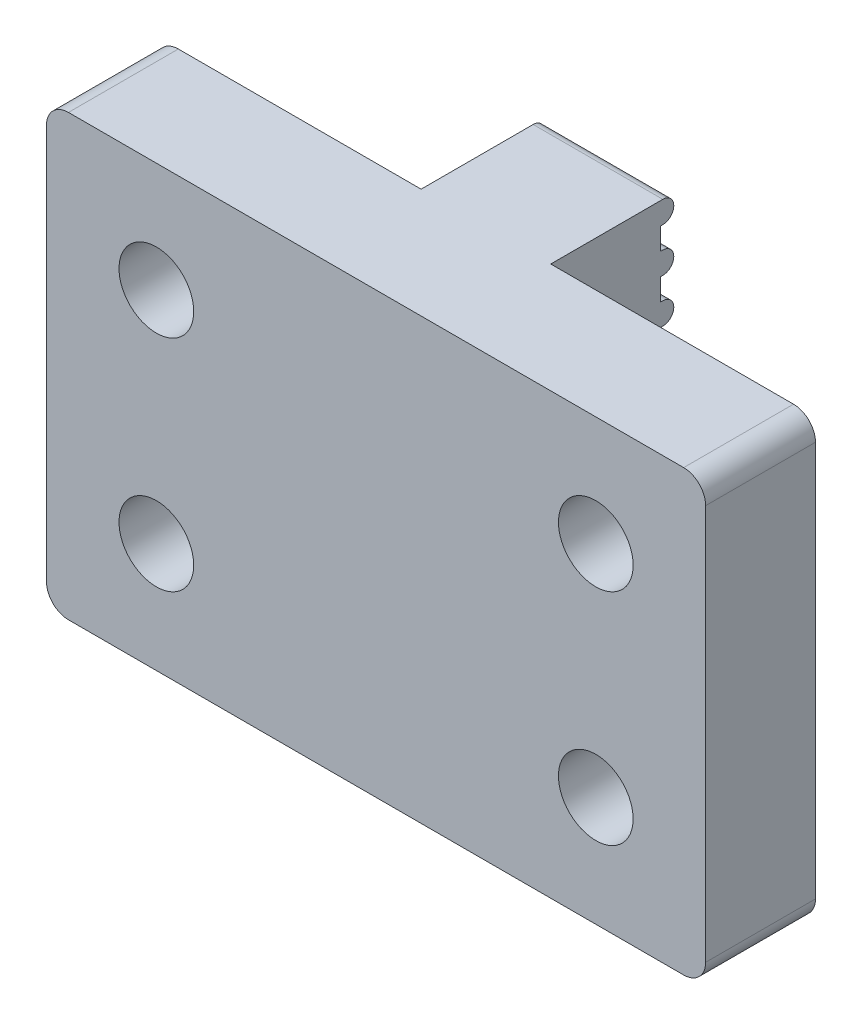
SolidWorks part; units mm, degrees
ref_plane "Front Plane" through (0, 0, 0) normal (0, 0, 1) x (1, 0, 0)
ref_plane "Top Plane" through (0, 0, 0) normal (0, 1, 0) x (1, 0, 0)
ref_plane "Right Plane" through (0, 0, 0) normal (1, 0, 0) x (0, 0, -1)
sketch "Master Sketch" plane through (0, 0, 0) normal (0, 0, 1) x (1, 0, 0)
  line L0 (-10, 5) -> (10, 5) construction
  line L1 (-2.95, -10) -> (2.95, -10)
  line L2 (-2.95, -10) -> (-2.95, 10)
  line L3 (-2.95, 10) -> (2.95, 10)
  line L4 (2.95, -10) -> (2.95, 10)
  line L5 (-2.95, -10) -> (2.95, 10) construction
  line L6 (-2.95, 10) -> (2.95, -10) construction
  line L7 (-15, -10) -> (15, -10)
  line L8 (-15, -10) -> (-15, 10)
  line L9 (-15, 10) -> (15, 10)
  line L10 (15, -10) -> (15, 10)
  line L11 (-15, -10) -> (15, 10) construction
  line L12 (-15, 10) -> (15, -10) construction
  line L13 (0, 0) -> (11.1967, 0) construction
  line L14 (-10, -5) -> (10, -5) construction
  point P0 (0, 0)
  point P5 (0, 0)
  point P14 (0, 0)
  dimension "D1" = 5.9
  dimension "D2" = 20
  dimension "D3" = 20
  dimension "D4" = 30
  dimension "D5" = 20
  dimension "D6" = 5
sketch "Outer Block Sketch" plane through (0, 0, 0) normal (0, 0, 1) x (1, 0, 0)
  line L0 (15, -10) -> (15, 10) construction
  line L1 (-15, -10) -> (15, -10) construction
  line L2 (-15, -10) -> (-15, 10) construction
  line L3 (-15, 10) -> (15, 10) construction
  line L4 (15, -10) -> (15, 10)
  line L5 (-15, -10) -> (15, -10)
  line L6 (-15, -10) -> (-15, 10)
  line L7 (-15, 10) -> (15, 10)
sketch "Belt Trap Block Sketch" plane through (0, 0, 0) normal (0, 0, 1) x (1, 0, 0)
  line L0 (-2.95, -10) -> (2.95, -10) construction
  line L1 (2.95, -10) -> (2.95, 10) construction
  line L2 (-2.95, 10) -> (2.95, 10) construction
  line L3 (-2.95, -10) -> (-2.95, 10) construction
  line L4 (-2.95, -10) -> (2.95, -10)
  line L5 (2.95, -10) -> (2.95, 10)
  line L6 (-2.95, 10) -> (2.95, 10)
  line L7 (-2.95, -10) -> (-2.95, 10)
extrude "Main Block" add sketch "Outer Block Sketch" along normal blind 5
extrude "Belt Trap Block" add sketch "Belt Trap Block Sketch" against normal blind 5
hole_wizard "M3 Clearance Hole1" positions "Sketch4" profile "Sketch6" hole size "M3" standard "ISO" end condition through all
sketch "Sketch4" plane through (0, 0, 5) normal (0, 0, 1) x (1, 0, 0)
  point P0 (-10, 5)
  point P3 (10, 5)
  point P8 (-10, -5)
  point P11 (10, -5)
sketch "Sketch6" plane through (-10, 5, 5) normal (1, 0, 0) x (0, -1, 0)
  line L0 (0, 0) -> (0, 10)
  line L1 (0, 10) -> (1.7, 10)
  line L2 (1.7, 10) -> (1.7, 0)
  line L5 (1.7, 0) -> (0, 0)
  line L11 (0, -6.35) -> (0, 107.95) construction
  dimension "Thru Hole Dia." = 3.4
  dimension "Thru Hole Depth" = 10
sketch "Belt Trapping Ridges Sketch" plane through (2.95, 0, 0) normal (1, 0, 0) x (0, 0, -1)
  line L0 (5, 10) -> (5.1, 10)
  line L1 (5, 10) -> (5, 9)
  line L2 (5.1, 9) -> (5, 9)
  line L3 (5, -10) -> (5, 10) construction
  arc A0 (5.1, 10) -> (5.1, 9) centre (5.1, 9.5) cw
  dimension "D1" = 0.5
  dimension "D2" = 0.1
extrude "Belt Trapping Ridge (Master)" add sketch "Belt Trapping Ridges Sketch" against normal up to surface (5.9 mm away) up to face at (-2.95, 0, -2.5)
pattern_linear "Belt Trapping Ridges Pattern" count 10 spacing 2 along (0, -1, 0) of "Belt Trapping Ridge (Master)"
fillet "Print Helper Fillets" radius 1 6 edges at (15, -10, 2.5) (15, 10, 2.5) (-15, -10, 2.5) (-15, 10, 2.5) (-2.95, -10, -2.5) (2.95, -10, -2.5)
